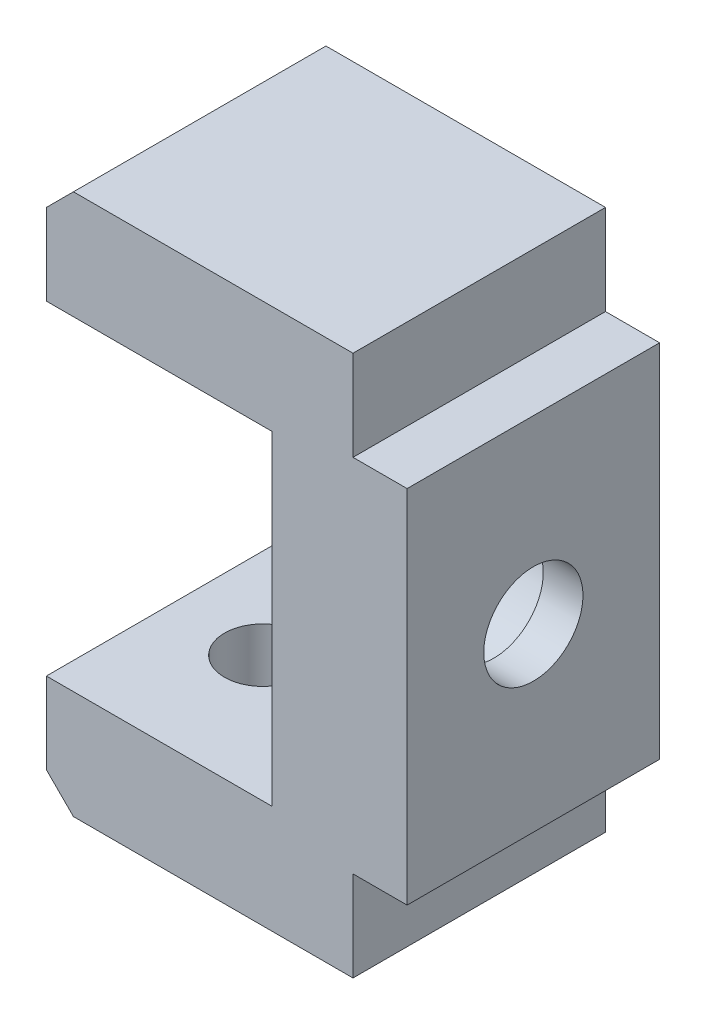
SolidWorks part; units mm, degrees
material "1.0503 (C45)"
ref_plane "Front Plane" through (0, 0, 0) normal (0, 0, 1) x (1, 0, 0)
ref_plane "Top Plane" through (0, 0, 0) normal (0, 1, 0) x (1, 0, 0)
ref_plane "Right Plane" through (0, 0, 0) normal (1, 0, 0) x (0, 0, -1)
sketch "Esquisse1" plane through (0, 0, 0) normal (0, 0, 1) x (1, 0, 0)
  line L0 (0, 0) -> (0, 10)
  line L1 (0, 10) -> (6, 10)
  line L2 (6, 10) -> (6, 50)
  line L3 (6, 50) -> (0, 50)
  line L4 (0, 50) -> (0, 60)
  line L5 (0, 60) -> (-34, 60)
  line L6 (-34, 60) -> (-34, 48)
  line L7 (-34, 48) -> (-9, 48)
  line L8 (-9, 48) -> (-9, 12)
  line L9 (-9, 12) -> (-34, 12)
  line L10 (-34, 12) -> (-34, 0)
  line L11 (-34, 0) -> (0, 0)
  dimension "D1" = 10
  dimension "D2" = 6
  dimension "D3" = 40
  dimension "D4" = 6
  dimension "D5" = 10
  dimension "D6" = 34
  dimension "D7" = 12
  dimension "D8" = 25
  dimension "D9" = 36
  dimension "D10" = 25
extrude "Boss.-Extru.1" add sketch "Esquisse1" along normal blind 28
chamfer "Chanfrein1" distance 3 angle 45 2 edges at (-34, 0, 14) (-34, 60, 14)
hole_wizard "Trou taraudé M101" positions "Esquisse2" profile "Esquisse3" tap size "M10" standard "ISO" end condition through all
sketch "Esquisse2" plane through (0, 12, 0) normal (0, 1, 0) x (1, 0, 0)
  line L0 (-9, -28) -> (-9, 0) construction
  line L1 (-9, -28) -> (-34, -28) construction
  point P0 (-24, -14)
  dimension "D1" = 15
  dimension "D2" = 14
sketch "Esquisse3" plane through (-24, 12, 14) normal (1, 0, 0) x (0, 0, 1)
  line L0 (0, 0) -> (0, 12)
  line L1 (0, 12) -> (6, 12)
  line L2 (4.25, 10.9896) -> (4.25, 0)
  line L5 (4.25, 0) -> (0, 0)
  line L7 (6, 12) -> (4.25, 10.9896)
  line L8 (-6, 12) -> (-4.25, 10.9896) construction
  line L11 (0, -6.35) -> (0, 107.95) construction
  dimension "Diamètre du trou pour taraudage jusqu'au prochain" = 8.5
  dimension "Profondeur du trou pour taraudage jusqu'au prochain" = 12
  dimension "Diamètre du fraisage débouchant" = 12
  dimension "Angle du fraisage débouchant" = 120
cosmetic thread "Filetage de perçage2"
hole_wizard "Chambrage pour vis à tête hexagonale M101" positions "Esquisse4" profile "Esquisse5" counterbore size "M10" standard "ISO" end condition through all
sketch "Esquisse4" plane through (-9, 0, 0) normal (-1, 0, 0) x (0, 0, 1)
  line L0 (28, 48) -> (0, 48) construction
  line L1 (28, 48) -> (28, 12) construction
  point P0 (14, 30)
  dimension "D1" = 18
  dimension "D2" = 14
sketch "Esquisse5" plane through (-9, 30, 14) normal (0, 1, 0) x (0, 0, 1)
  line L0 (0, 0) -> (0, 15)
  line L1 (0, 15) -> (5.5, 15)
  line L3 (5.5, 15) -> (5.5, 10.6)
  line L4 (5.5, 10.6) -> (9, 10.6)
  line L5 (9, 10.6) -> (9, 0)
  line L7 (9, 0) -> (0, 0)
  line L11 (0, -6.35) -> (0, 107.95) construction
  dimension "Diamètre du perçage jusqu'au prochain" = 11
  dimension "Profondeur du perçage jusqu'au prochain" = 15
  dimension "Diamètre du chambrage" = 18
  dimension "Profondeur du chambrage" = 10.6
